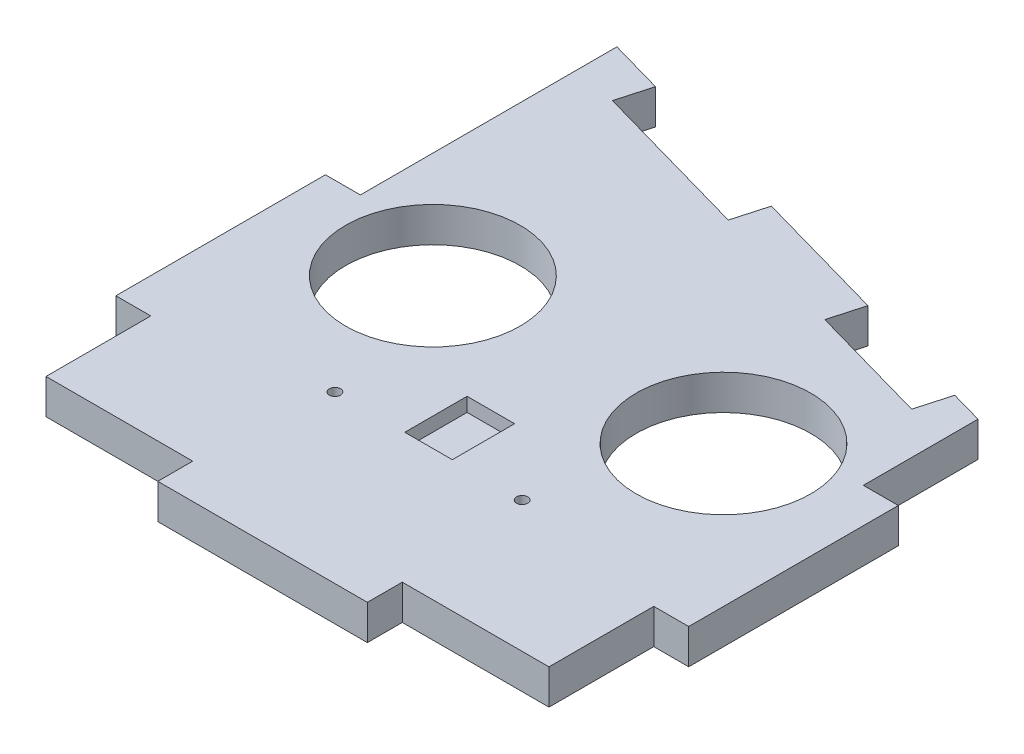
SolidWorks part; units mm, degrees
ref_plane "Front Plane" through (0, 0, 0) normal (0, 0, 1) x (1, 0, 0)
ref_plane "Top Plane" through (0, 0, 0) normal (0, 1, 0) x (1, 0, 0)
ref_plane "Right Plane" through (0, 0, 0) normal (1, 0, 0) x (0, 0, -1)
sketch "Sketch1" plane through (0, 0, 0) normal (0, 1, 0) x (1, 0, 0)
  line L0 (16.51, 0) -> (3.175, 0)
  line L1 (16.51, 0) -> (16.51, -3.175)
  line L2 (16.51, -3.175) -> (35.56, -3.175)
  line L3 (35.56, -3.175) -> (35.56, 0)
  line L4 (35.56, 0) -> (48.895, 0)
  line L5 (48.895, 0) -> (48.895, 9.525)
  line L6 (52.07, 9.525) -> (48.895, 9.525)
  line L7 (45.9585, 39.824) -> (48.895, 38.9956)
  line L8 (48.895, 28.575) -> (52.07, 28.575)
  line L9 (48.895, 38.9956) -> (52.07, 38.1) construction
  line L10 (52.07, 28.575) -> (52.07, 9.525)
  line L11 (8.0672, 50.5125) -> (3.175, 51.8925)
  line L12 (0, 28.575) -> (3.175, 28.575)
  line L13 (0, 28.575) -> (0, 9.525)
  line L14 (3.175, 9.525) -> (0, 9.525)
  line L16 (52.07, 38.1) -> (31.283, 38.1) construction
  line L17 (12.827, 25.5124) -> (39.243, 25.5124) construction
  line L18 (26.035, 25.5124) -> (26.035, -3.175) construction
  line L19 (45.9585, 39.824) -> (45.0965, 36.7682)
  line L20 (45.0965, 36.7682) -> (34.0958, 39.8713)
  line L21 (34.0958, 39.8713) -> (34.9578, 42.9271)
  line L22 (34.9578, 42.9271) -> (22.7348, 46.375)
  line L23 (22.7348, 46.375) -> (21.8728, 43.3193)
  line L24 (21.8728, 43.3193) -> (7.2052, 47.4568)
  line L25 (7.2052, 47.4568) -> (8.0672, 50.5125)
  line L27 (3.175, 28.575) -> (3.175, 51.8925)
  line L28 (3.175, 9.525) -> (3.175, 0)
  line L29 (48.895, 28.575) -> (48.895, 38.9956)
  line L30 (48.895, 9.525) -> (48.895, 0) construction
  circle A0 centre (12.827, 25.5124) radius 7.9375
  circle A1 centre (39.243, 25.5124) radius 7.9375
  dimension "D1" = 15.875
  dimension "D2" = 19.05
  dimension "D3" = 3.175
  dimension "D5" = 3.175
  dimension "D6" = 19.05
  dimension "D7" = 19.05
  dimension "D8" = 26.416
  dimension "D9" = 15.24
  dimension "D10" = 11.43
  dimension "D12" = 12.7
  dimension "D15" = 51.8925
  dimension "D16" = 38.9956
extrude "Boss-Extrude1" add sketch "Sketch1" along normal blind 3.175
sketch "Sketch2" plane through (0, 3.175, 0) normal (0, 1, 0) x (1, 0, 0)
  line L0 (39.243, 17.5749) -> (20.6827, 17.5749) construction
  line L1 (23.876, 17.5749) -> (28.194, 17.5749)
  line L2 (23.876, 17.5749) -> (23.876, 11.9107)
  line L3 (23.876, 11.9107) -> (28.194, 11.9107)
  line L4 (28.194, 17.5749) -> (28.194, 11.9107)
  line L5 (26.035, -3.175) -> (26.035, 11.9107) construction
  line L6 (16.51, -3.175) -> (35.56, -3.175) construction
  circle A0 centre (39.243, 25.5124) radius 7.9375 construction
  dimension "D1" = 5.6642
  dimension "D2" = 4.318
extrude "Cut-Extrude1" cut sketch "Sketch2" against normal blind 1.27
sketch "Sketch3" plane through (0, 3.175, 0) normal (0, 1, 0) x (1, 0, 0)
  line L0 (23.876, 11.9107) -> (17.526, 11.9107) construction
  line L1 (28.194, 11.9107) -> (34.544, 11.9107) construction
  circle A0 centre (17.526, 11.9107) radius 0.508
  circle A1 centre (34.544, 11.9107) radius 0.508
  dimension "D1" = 1.016
  dimension "D2" = 6.35
extrude "Cut-Extrude2" cut sketch "Sketch3" against normal through all
